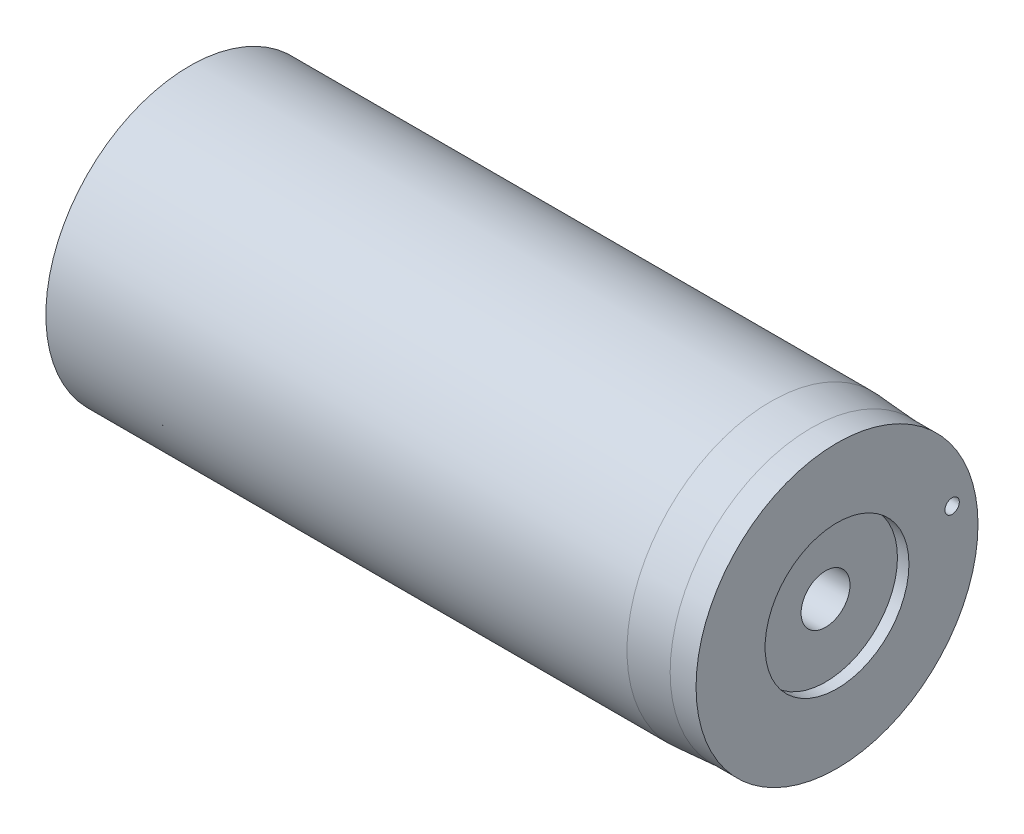
SolidWorks part; units mm, degrees
ref_plane "Plan de face" through (0, 0, 0) normal (0, 0, 1) x (1, 0, 0)
ref_plane "Plan de dessus" through (0, 0, 0) normal (0, 1, 0) x (1, 0, 0)
ref_plane "Plan de droite" through (0, 0, 0) normal (1, 0, 0) x (0, 0, -1)
sketch "Esquisse1" plane through (0, 0, 0) normal (0, 0, 1) x (1, 0, 0)
  line L0 (0, 0) -> (-284.173, 0) construction
  line L1 (-0.7618, 25) -> (-0.7618, 49)
  line L2 (-0.7618, 49) -> (-9.7618, 49)
  line L3 (-217.4618, 48) -> (-221.7618, 48) construction
  line L4 (-9.7618, 49) -> (-23.7618, 50)
  line L5 (-23.7618, 50) -> (-225.7618, 50)
  line L6 (-225.7618, 50) -> (-225.7618, 48.5)
  line L7 (-225.7618, 48.5) -> (-221.7618, 48.5)
  line L8 (-221.7618, 48.5) -> (-221.7618, 48)
  line L9 (-213.856, 44.5) -> (-9.7618, 44.5)
  line L10 (-9.7618, 44.5) -> (-9.7618, 15)
  line L11 (-124.7618, 8.5) -> (-4.7618, 8.5)
  line L12 (-4.7618, 8.5) -> (-4.7618, 25)
  line L13 (-4.7618, 25) -> (-0.7618, 25)
  line L14 (-214.2618, 48) -> (-221.7618, 48)
  line L15 (-9.7618, 15) -> (-24.7618, 15)
  line L17 (-24.7618, 15) -> (-24.7618, 12.5)
  line L18 (-24.7618, 12.5) -> (-64.7618, 12.5)
  line L20 (-214.2618, 45.503) -> (-214.2618, 48)
  line L21 (-64.7618, 12.5) -> (-64.7618, 10)
  line L23 (-64.7618, 10) -> (-124.7618, 10)
  line L24 (-124.7618, 10) -> (-124.7618, 8.5)
  arc A0 (-213.856, 44.5) -> (-214.2618, 45.503) centre (-325.3, 0) ccw
  dimension "D1" = 17
  dimension "D2" = 50
  dimension "D3" = 5
  dimension "D4" = 4
  dimension "D5" = 100
  dimension "D6" = 98
  dimension "D7" = 14
  dimension "D8" = 9
  dimension "D9" = 202
  dimension "D10" = 1.5
  dimension "D11" = 4
  dimension "D13" = 89
  dimension "D14" = 20
  dimension "D15" = 120
  dimension "D16" = 25
  dimension "D17" = 30
  dimension "D18" = 15
  dimension "D19" = 40
  dimension "D20" = 7.5
revolve "Révolution1" add sketch "Esquisse1" angle 360 about L0
hole_wizard "Trou taraudé M61" positions "Esquisse4" profile "Esquisse3" tap size "M6" standard "ISO" end condition through all
sketch "Esquisse4" plane through (-0.7618, 0, 0) normal (1, 0, 0) x (0, 0, -1)
  point P0 (40, 10)
sketch "Esquisse3" plane through (-0.7618, 10, -40) normal (0, 1, 0) x (0, 0, -1)
  line L0 (0, 0) -> (0, 225)
  line L1 (0, 225) -> (2.5, 225)
  line L2 (2.5, 225) -> (2.5, 0)
  line L5 (2.5, 0) -> (0, 0)
  line L11 (0, -6.35) -> (0, 107.95) construction
  dimension "Diamètre du trou pour taraudage jusqu'au prochain" = 5
  dimension "Profondeur du trou pour taraudage jusqu'au prochain" = 225
cosmetic thread "Filetage de perçage1" parameters "D2"=6
